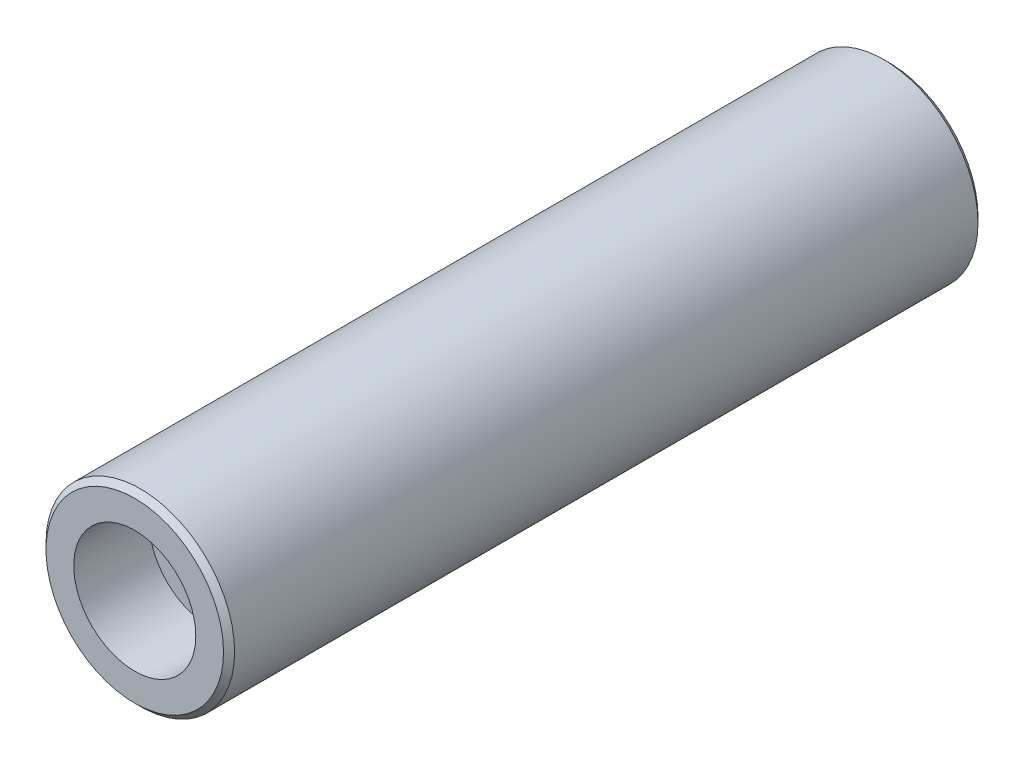
SolidWorks part; units mm, degrees
ref_plane "前视基准面" through (0, 0, 0) normal (0, 0, 1) x (1, 0, 0)
ref_plane "上视基准面" through (0, 0, 0) normal (0, 1, 0) x (1, 0, 0)
ref_plane "右视基准面" through (0, 0, 0) normal (1, 0, 0) x (0, 0, -1)
sketch "草图1" plane through (0, 0, 0) normal (0, 0, 1) x (1, 0, 0)
  circle A0 centre (-11.7255, -50.9374) radius 8.5
  dimension "D1" = 17
extrude "凸台-拉伸1" add sketch "草图1" along normal blind 68
hole_wizard "打孔尺寸(%根据)内六角圆柱头螺钉的类型1" positions "草图4" profile "草图3" counterbore size "M6" standard "GB" end condition through all
sketch "草图4" plane through (0, 0, 68) normal (0, 0, 1) x (1, 0, 0)
  point P0 (-11.7255, -50.9374)
sketch "草图3" plane through (-11.7255, -50.9374, 68) normal (1, 0, 0) x (0, -1, 0)
  line L0 (0, 0) -> (0, 68)
  line L1 (0, 68) -> (3.5, 68)
  line L3 (3.5, 68) -> (3.5, 6.8)
  line L4 (3.5, 6.8) -> (5.5, 6.8)
  line L5 (5.5, 6.8) -> (5.5, 0)
  line L7 (5.5, 0) -> (0, 0)
  line L11 (0, -6.35) -> (0, 107.95) construction
  dimension "通孔孔直径" = 7
  dimension "通孔孔深度" = 68
  dimension "柱形沉头孔直径" = 11
  dimension "柱形沉头孔深度" = 6.8
chamfer "倒角1" distance 0.5 angle 45 2 edges at (-3.2255, -50.9374, 0) (-3.2255, -50.9374, 68)
